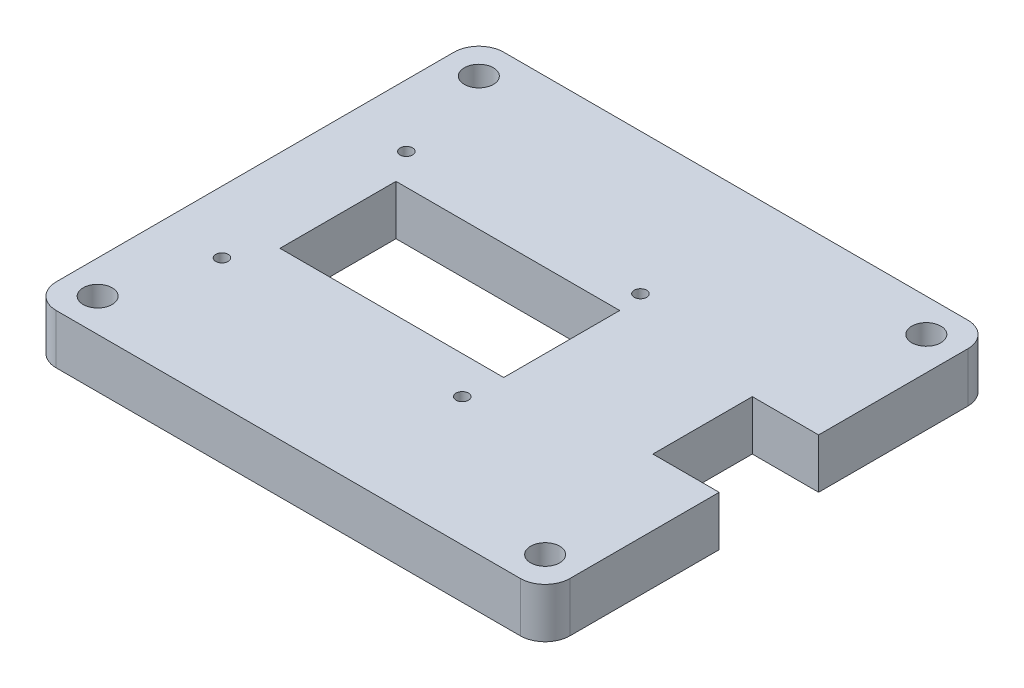
SolidWorks part; units mm, degrees
ref_plane "Front Plane" through (0, 0, 0) normal (0, 0, 1) x (1, 0, 0)
ref_plane "Top Plane" through (0, 0, 0) normal (0, 1, 0) x (1, 0, 0)
ref_plane "Right Plane" through (0, 0, 0) normal (1, 0, 0) x (0, 0, -1)
sketch "Sketch1" plane through (0, 0, 0) normal (0, 1, 0) x (1, 0, 0)
  line L1 (0, 0) -> (27, 0)
  line L2 (0, 0) -> (0, -14)
  line L3 (0, -14) -> (27, -14)
  line L4 (27, 0) -> (27, -14)
  line L5 (-10, 20) -> (52, 20)
  line L6 (-10, 20) -> (-10, -34)
  line L7 (-10, -34) -> (52, -34)
  line L8 (52, 20) -> (52, -34)
  dimension "D1" = 27
  dimension "D2" = 14
  dimension "D3" = 10
  dimension "D4" = 20
  dimension "D5" = 20
  dimension "D6" = 25
extrude "Boss-Extrude1" add sketch "Sketch1" along normal blind 6
sketch "Sketch2" plane through (0, 6, 0) normal (0, 1, 0) x (1, 0, 0)
  line L0 (0, -7) -> (27, -7) construction
  line L1 (0, 0) -> (0, -14) construction
  line L2 (27, -14) -> (27, 0) construction
  circle A0 centre (-2.5, 3.75) radius 0.75
  circle A1 centre (-2.5, -18.5) radius 0.75
  circle A2 centre (26.5, 3) radius 0.75
  circle A3 centre (26.5, -18.5) radius 0.75
  dimension "D1" = 1.5
  dimension "D5" = 29
  dimension "D2" = 10.75
  dimension "D3" = 11.5
  dimension "D4" = 2.5
  dimension "D6" = 10
  dimension "D7" = 11.5
extrude "Cut-Extrude1" cut sketch "Sketch2" against normal through all
sketch "Sketch3" plane through (0, 6, 0) normal (0, 1, 0) x (1, 0, 0)
  line L0 (-10, 20) -> (-10, -34) construction
  line L1 (52, 20) -> (-10, 20) construction
  line L2 (-10, -34) -> (52, -34) construction
  line L3 (52, -34) -> (52, 20) construction
  circle A0 centre (-6, 16) radius 1.75
  circle A1 centre (-6, -30) radius 1.75
  circle A2 centre (48, 16) radius 1.75
  circle A3 centre (48, -30) radius 1.75
  dimension "D1" = 3.5
  dimension "D2" = 4
  dimension "D3" = 4
  dimension "D4" = 4
  dimension "D5" = 4
  dimension "D6" = 4
  dimension "D7" = 4
  dimension "D8" = 4
  dimension "D9" = 4
extrude "Cut-Extrude2" cut sketch "Sketch3" against normal through all
fillet "Fillet1" radius 3 4 edges at (-10, 3, -20) (-10, 3, 34) (52, 3, -20) (52, 3, 34)
sketch "Sketch4" plane through (0, 6, 0) normal (0, 1, 0) x (1, 0, 0)
  line L0 (52, -7) -> (-10, -7) construction
  line L1 (52, -31) -> (52, 17) construction
  line L2 (-10, 17) -> (-10, -31) construction
  line L4 (60, -13) -> (44, -13)
  line L5 (60, -13) -> (60, -1)
  line L6 (60, -1) -> (44, -1)
  line L7 (44, -13) -> (44, -1)
  line L8 (60, -13) -> (44, -1) construction
  line L9 (60, -1) -> (44, -13) construction
  dimension "D1" = 12
  dimension "D2" = 8
extrude "Cut-Extrude3" cut sketch "Sketch4" against normal through all
equation "\"D3@Sketch3\"=\"D2@Sketch3\""
equation "\"D4@Sketch3\"=\"D2@Sketch3\""
equation "\"D5@Sketch3\"=\"D2@Sketch3\""
equation "\"D6@Sketch3\"=\"D2@Sketch3\""
equation "\"D7@Sketch3\"=\"D2@Sketch3\""
equation "\"D8@Sketch3\"=\"D2@Sketch3\""
equation "\"D9@Sketch3\"=\"D2@Sketch3\""
